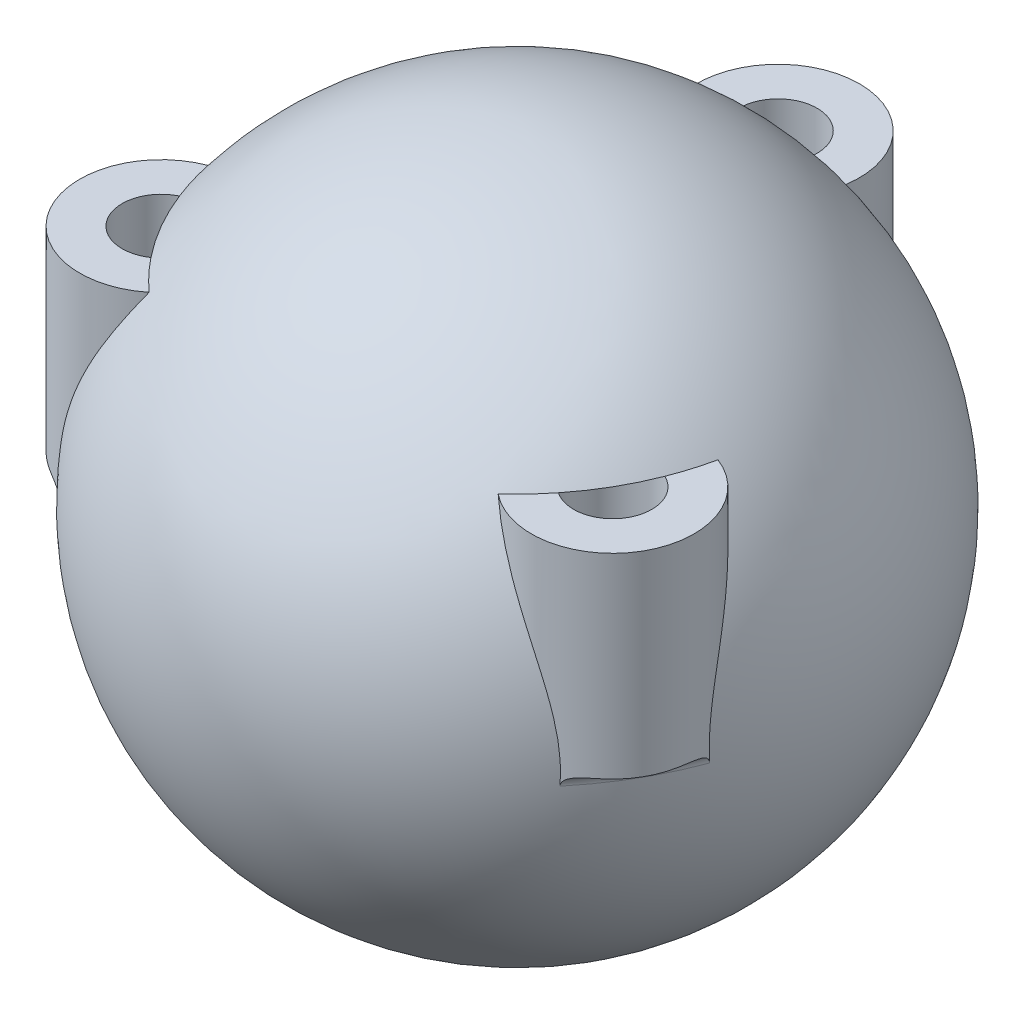
SolidWorks part; units mm, degrees
material "Cast Carbon Steel"
ref_plane "Front Plane" through (0, 0, 0) normal (0, 0, 1) x (1, 0, 0)
ref_plane "Top Plane" through (0, 0, 0) normal (0, 1, 0) x (1, 0, 0)
ref_plane "Right Plane" through (0, 0, 0) normal (1, 0, 0) x (0, 0, -1)
sketch "Sketch1" plane through (0, 0, 0) normal (0, 0, 1) x (1, 0, 0)
  line L0 (-50, 0) -> (50, 0)
  arc A0 (50, 0) -> (-50, 0) centre (0, 0) ccw
  arc A1 (38, 0) -> (-38, 0) centre (0, 0) ccw
  point P4 (0, 0)
revolve "Revolve1" add sketch "Sketch1" angle 360 about L0
sketch "Sketch2" plane through (0, 0, 0) normal (0, 1, 0) x (1, 0, 0)
  circle A0 centre (0, 40) radius 12.5
  circle A1 centre (34.641, -20) radius 12.5
  circle A2 centre (-34.641, -20) radius 12.5
  point P8 (0, 0)
  dimension "D1" = 3
extrude "Boss-Extrude3" add sketch "Sketch2" along normal blind 30
sketch "Sketch3" plane through (0, 30, 0) normal (0, 1, 0) x (1, 0, 0)
  circle A0 centre (0, 40) radius 6
  arc A1 (12.3465, 38.0469) -> (-12.3465, 38.0469) centre (0, 0) ccw construction
  circle A2 centre (34.641, -20) radius 6
  circle A3 centre (-34.641, -20) radius 6
  point P12 (0, 0)
  dimension "D1" = 3
extrude "Cut-Extrude1" cut sketch "Sketch3" against normal blind 15
fillet "Fillet1" radius 2 3 edges at (0, 0, -50) (-43.3013, 0, 25) (43.3013, 0, 25)
sketch "Sketch4" plane through (0, 0, 0) normal (0, 1, 0) x (1, 0, 0)
  circle A0 centre (0, 0) radius 12
extrude "Cut-Extrude2" cut sketch "Sketch4" against normal through all
